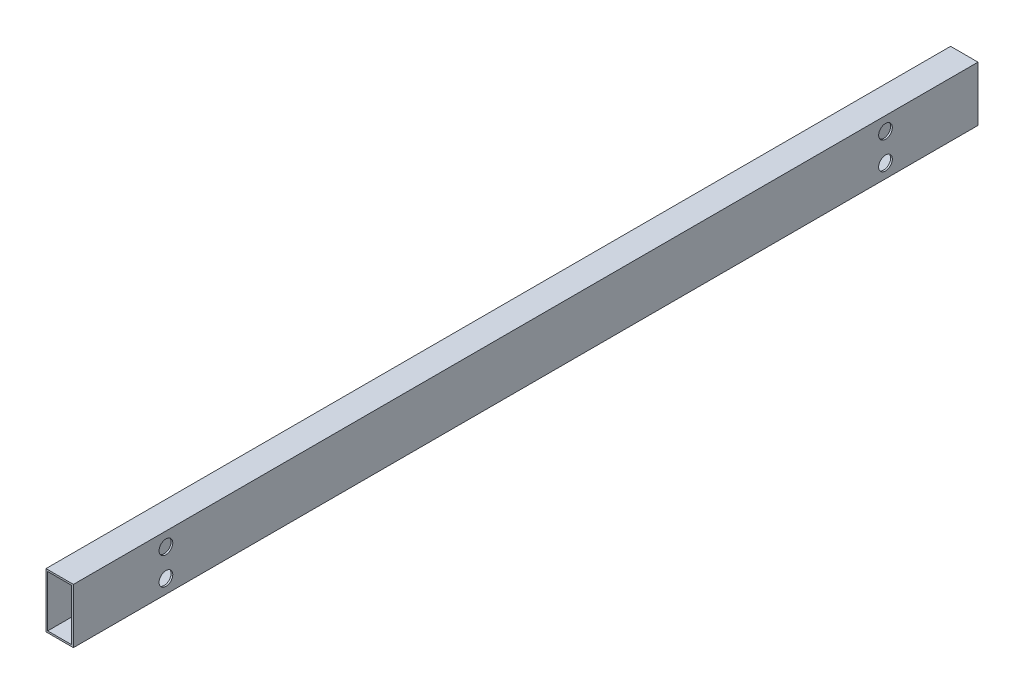
SolidWorks part; units mm, degrees
ref_plane "Front Plane" through (0, 0, 0) normal (0, 0, 1) x (1, 0, 0)
ref_plane "Top Plane" through (0, 0, 0) normal (0, 1, 0) x (1, 0, 0)
ref_plane "Right Plane" through (0, 0, 0) normal (1, 0, 0) x (0, 0, -1)
sketch "Sketch1" plane through (0, 0, 0) normal (0, 0, 1) x (1, 0, 0)
  line L1 (-12.7, -25.4) -> (12.7, -25.4)
  line L2 (-12.7, -25.4) -> (-12.7, 25.4)
  line L3 (-12.7, 25.4) -> (12.7, 25.4)
  line L4 (12.7, -25.4) -> (12.7, 25.4)
  line L5 (-12.7, -25.4) -> (12.7, 25.4) construction
  line L6 (-12.7, 25.4) -> (12.7, -25.4) construction
  line L7 (-11.1125, -23.8125) -> (11.1125, -23.8125)
  line L8 (-11.1125, -23.8125) -> (-11.1125, 23.8125)
  line L9 (-11.1125, 23.8125) -> (11.1125, 23.8125)
  line L10 (11.1125, -23.8125) -> (11.1125, 23.8125)
  line L11 (-11.1125, -23.8125) -> (11.1125, 23.8125) construction
  line L12 (-11.1125, 23.8125) -> (11.1125, -23.8125) construction
  point P0 (0, 0)
  point P1 (0, 0)
  point P7 (0, 0)
  dimension "D1" = 25.4
  dimension "D2" = 50.8
  dimension "D3" = 1.5875
  dimension "D4" = 1.5875
extrude "Boss-Extrude1" add sketch "Sketch1" along normal blind 838.2
sketch "Sketch2" plane through (12.7, 0, 0) normal (1, 0, 0) x (0, 0, -1)
  line L0 (-85.725, 25.4) -> (-85.725, -25.4) construction
  line L1 (-73.025, 25.4) -> (-98.425, 25.4) construction
  line L2 (-73.025, 25.4) -> (-73.025, -25.4) construction
  line L3 (-73.025, -25.4) -> (-98.425, -25.4) construction
  line L4 (-98.425, 25.4) -> (-98.425, -25.4) construction
  line L6 (-838.2, 25.4) -> (0, 25.4) construction
  line L7 (-838.2, -25.4) -> (0, -25.4) construction
  line L8 (0, -25.4) -> (0, 25.4) construction
  line L9 (-765.175, 25.4) -> (-739.775, 25.4) construction
  line L10 (-765.175, 25.4) -> (-765.175, -25.4) construction
  line L11 (-765.175, -25.4) -> (-739.775, -25.4) construction
  line L12 (-739.775, 25.4) -> (-739.775, -25.4) construction
  line L13 (-838.2, -25.4) -> (-838.2, 25.4) construction
  line L14 (-752.475, 25.4) -> (-752.475, -25.4) construction
  circle A0 centre (-85.725, 12.7) radius 3.175
  circle A1 centre (-85.725, -12.7) radius 3.175
  circle A2 centre (-752.475, 12.7) radius 3.175
  circle A3 centre (-752.475, -12.7) radius 3.175
  dimension "D6" = 6.35
  dimension "D2" = 25.4
  dimension "D3" = 50.8
  dimension "D4" = 25.4
  dimension "D1" = 73.025
  dimension "D5" = 73.025
  dimension "D7" = 12.7
  dimension "D8" = 25.4
extrude "Cut-Extrude1" cut sketch "Sketch2" against normal through all
sketch "Sketch3" plane through (12.7, 0, 0) normal (1, 0, 0) x (0, 0, -1)
  circle A0 centre (-752.475, 12.7) radius 6.35
  circle A1 centre (-752.475, -12.7) radius 6.35
  circle A2 centre (-85.725, 12.7) radius 6.35
  circle A3 centre (-85.725, -12.7) radius 6.35
  dimension "D1" = 12.7
extrude "Cut-Extrude2" cut sketch "Sketch3" against normal up to next
equation "\"D1@Sketch2\"=\"D5@Sketch2\""
